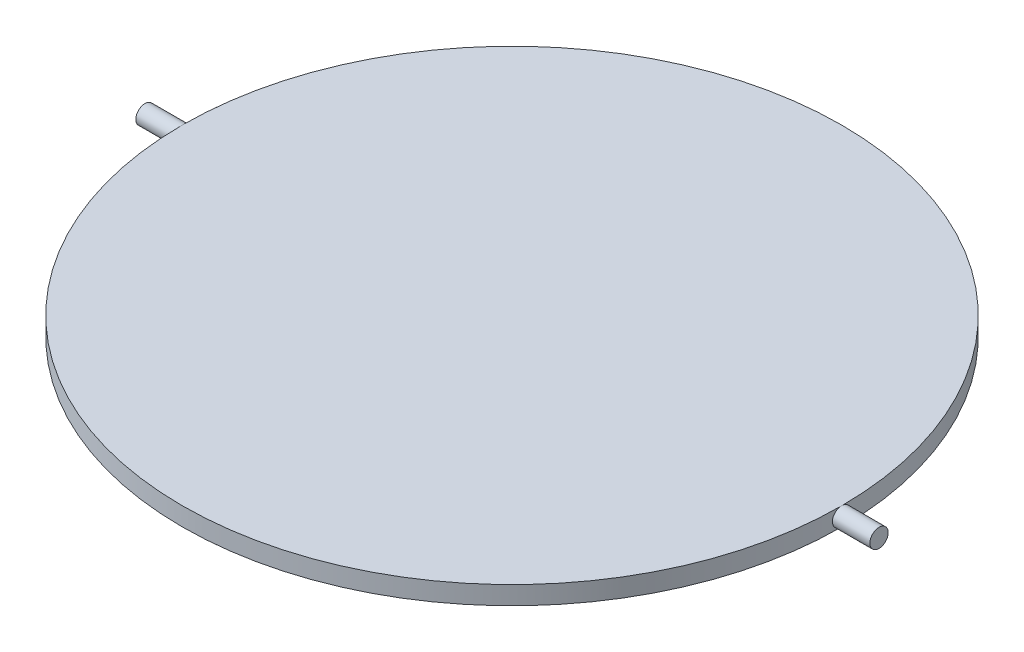
SolidWorks part; units mm, degrees
ref_plane "Front Plane" through (0, 0, 0) normal (0, 0, 1) x (1, 0, 0)
ref_plane "Top Plane" through (0, 0, 0) normal (0, 1, 0) x (1, 0, 0)
ref_plane "Right Plane" through (0, 0, 0) normal (1, 0, 0) x (0, 0, -1)
sketch "Sketch2" plane through (0, 0, 0) normal (0, 1, 0) x (1, 0, 0)
  line L0 (0, 26.95) -> (0, -26.95)
  circle A0 centre (0, 0) radius 26.95
  dimension "D1" = 53.9
extrude "Boss-Extrude3" add sketch "Sketch2" along normal mid plane 1.5 contours L0 A0 | L0 A0
sketch "Sketch6" plane through (0, 0, 0) normal (1, 0, 0) x (0, 0, -1)
  circle A0 centre (0, 0) radius 0.75
extrude "Boss-Extrude4" add sketch "Sketch6" along normal mid plane 60
